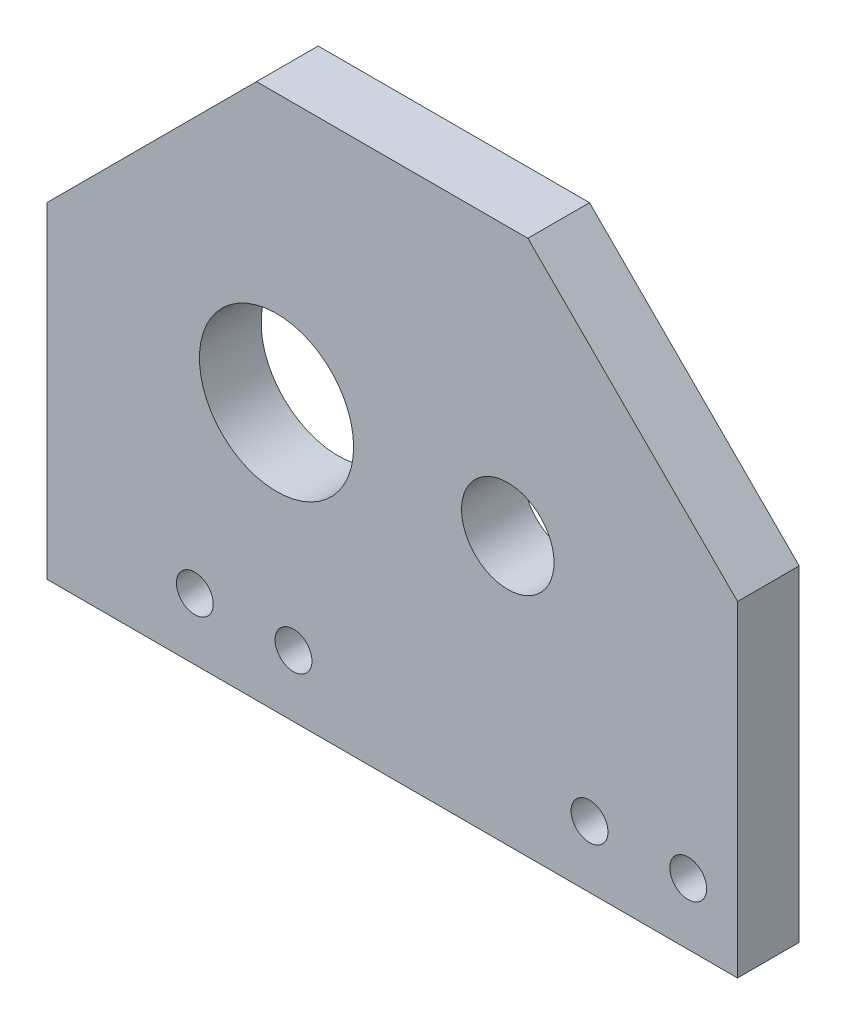
SolidWorks part; units mm, degrees
ref_plane "Front Plane" through (0, 0, 0) normal (0, 0, 1) x (1, 0, 0)
ref_plane "Top Plane" through (0, 0, 0) normal (0, 1, 0) x (1, 0, 0)
ref_plane "Right Plane" through (0, 0, 0) normal (1, 0, 0) x (0, 0, -1)
sketch "Sketch1" plane through (0, 0, 0) normal (0, 0, 1) x (1, 0, 0)
  line L1 (35.56, -27.5819) -> (-35.56, -27.5819)
  line L2 (35.56, -27.5819) -> (35.56, 27.5819)
  line L3 (35.56, 27.5819) -> (-35.56, 27.5819)
  line L4 (-35.56, -27.5819) -> (-35.56, 27.5819)
  line L5 (35.56, -27.5819) -> (-35.56, 27.5819) construction
  line L6 (35.56, 27.5819) -> (-35.56, -27.5819) construction
  circle A0 centre (11.9062, 0) radius 4.7625
  circle A1 centre (-11.9062, 0) radius 7.9375
  point P0 (0, 0)
  dimension "D3" = 9.525
  dimension "D6" = 15.875
  dimension "D1" = 71.12
  dimension "D2" = 55.1637
  dimension "D4" = 0
  dimension "D5" = 0
  dimension "D7" = 11.9062
  dimension "D8" = 11.9062
extrude "Boss-Extrude1" add sketch "Sketch1" along normal blind 6.35
hole_wizard "#6 Clearance Hole1" positions "Sketch2" profile "Sketch3" hole size "#6" standard "ANSI Inch" end condition through all
sketch "Sketch2" plane through (0, 0, 6.35) normal (0, 0, 1) x (1, 0, 0)
  line L0 (-20.32, -21.2319) -> (-10.16, -21.2319)
  line L2 (20.32, -21.2319) -> (30.48, -21.2319)
  line L4 (-35.56, -27.5819) -> (35.56, -27.5819) construction
  line L5 (-35.56, 27.5819) -> (-35.56, -27.5819) construction
  point P0 (-20.32, -21.2319)
  point P2 (-10.16, -21.2319)
  point P4 (20.32, -21.2319)
  point P6 (30.48, -21.2319)
  dimension "D1" = 10.16
  dimension "D2" = 10.16
  dimension "D3" = 6.35
  dimension "D4" = 6.35
  dimension "D5" = 15.24
  dimension "D6" = 30.48
sketch "Sketch3" plane through (-20.32, -21.2319, 6.35) normal (1, 0, 0) x (0, -1, 0)
  line L0 (0, 0) -> (0, 6.35)
  line L1 (0, 6.35) -> (1.8986, 6.35)
  line L2 (1.8986, 6.35) -> (1.8986, 0)
  line L5 (1.8986, 0) -> (0, 0)
  line L11 (0, -6.35) -> (0, 107.95) construction
  dimension "Thru Hole Dia." = 3.7973
  dimension "Thru Hole Depth" = 6.35
sketch "Sketch4" plane through (0, 0, 6.35) normal (0, 0, 1) x (1, 0, 0)
  line L0 (-35.56, 5.9919) -> (-35.56, 27.5819)
  line L1 (-35.56, 27.5819) -> (-35.56, -27.5819) construction
  line L2 (-35.56, 27.5819) -> (-13.97, 27.5819)
  line L3 (35.56, 27.5819) -> (-35.56, 27.5819) construction
  line L4 (-13.97, 27.5819) -> (-35.56, 5.9919)
  line L5 (13.97, 27.5819) -> (35.56, 27.5819)
  line L6 (35.56, 27.5819) -> (35.56, 5.9919)
  line L7 (35.56, -27.5819) -> (35.56, 27.5819) construction
  line L8 (35.56, 5.9919) -> (13.97, 27.5819)
  dimension "D1" = 21.59
  dimension "D2" = 21.59
  dimension "D3" = 21.59
  dimension "D4" = 21.59
extrude "Cut-Extrude1" cut sketch "Sketch4" against normal through all
